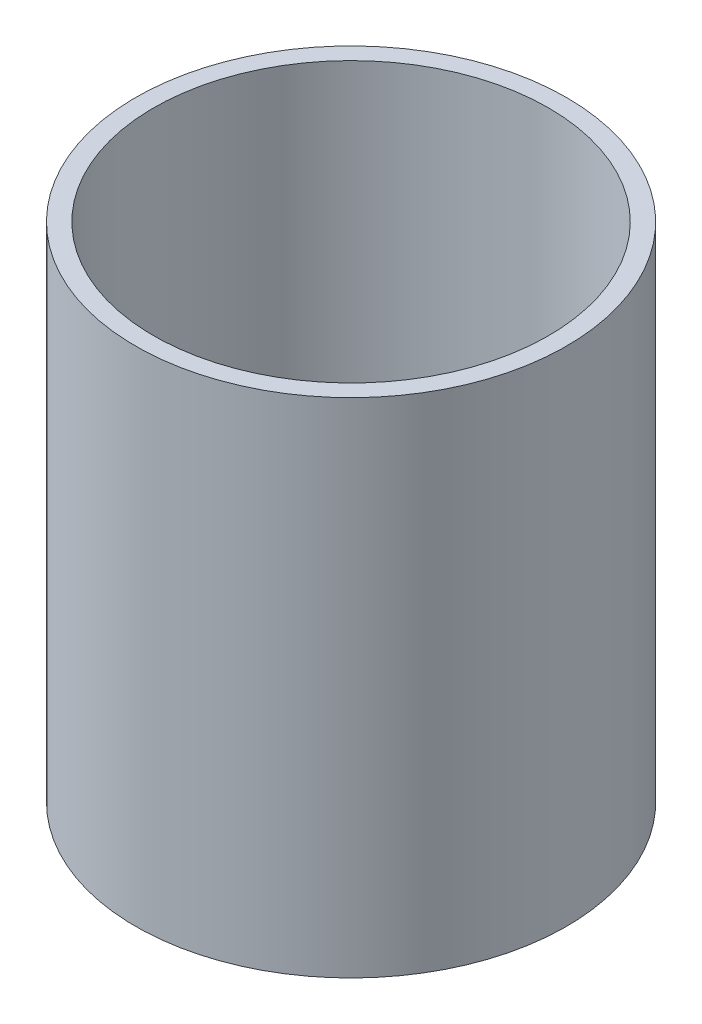
SolidWorks part; units mm, degrees
ref_plane "Front Plane" through (0, 0, 0) normal (0, 0, 1) x (1, 0, 0)
ref_plane "Top Plane" through (0, 0, 0) normal (0, 1, 0) x (1, 0, 0)
ref_plane "Right Plane" through (0, 0, 0) normal (1, 0, 0) x (0, 0, -1)
sketch "Sketch1" plane through (0, 0, 0) normal (0, 1, 0) x (1, 0, 0)
  circle A0 centre (0, 0) radius 18
  dimension "D1" = 36
extrude "Boss-Extrude1" add sketch "Sketch1" along normal blind 42 contours A0
sketch "Sketch4" plane through (0, 0, 0) normal (0, -1, 0) x (1, 0, 0)
  circle A0 centre (0, 0) radius 16.5
  dimension "D1" = 33
extrude "Cut-Extrude2" cut sketch "Sketch4" against normal blind 42
equation "\"stopper_dia\"= 36mm"
equation "\"shaft_dia\"= 29mm"
equation "\"D1@Sketch1\"=\"stopper_dia\""
equation "\"led_width\"= 12.4mm"
equation "\"led_height\"= 4.4mm"
equation "\"nut_depth\"= 5mm"
equation "\"button_dia\"= 22mm"
equation "\"nut_width\"= 25mm"
equation "\"D1@Sketch4\"=\"stopper_dia\"-3"
equation "\"height\"= 42mm"
equation "\"D1@Cut-Extrude2\"= \"height\""
equation "\"D1@Boss-Extrude1\"=\"height\""
